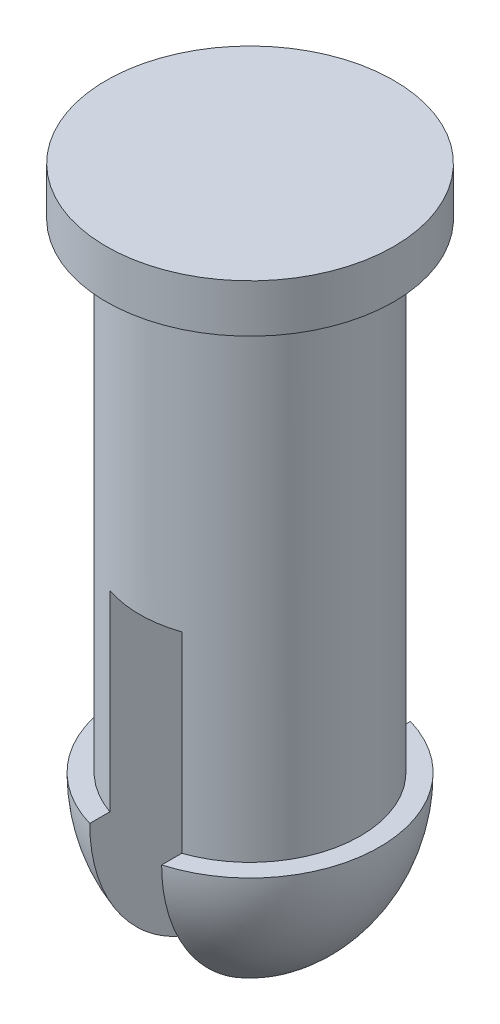
SolidWorks part; units mm, degrees
material "PVC Rigid"
ref_plane "Front Plane" through (0, 0, 0) normal (0, 0, 1) x (1, 0, 0)
ref_plane "Top Plane" through (0, 0, 0) normal (0, 1, 0) x (1, 0, 0)
ref_plane "Right Plane" through (0, 0, 0) normal (1, 0, 0) x (0, 0, -1)
sketch "Sketch1" plane through (0, 0, 0) normal (0, 0, 1) x (1, 0, 0)
  line L0 (0, 0) -> (0, 1.651)
  line L1 (0, 1.651) -> (0.381, 1.651)
  line L2 (0.381, 1.651) -> (0.381, 1.524)
  line L3 (0.381, 1.524) -> (0.2921, 1.524)
  line L4 (0.2921, 1.524) -> (0.2921, 0.254)
  line L5 (0.2921, 0.254) -> (0.3429, 0.254)
  line L6 (0, -0.1778) -> (0, 0)
  line L7 (0, -1000) -> (0, 49000) construction
  arc A0 (0.3429, 0.254) -> (0, -0.1778) centre (-0.1004, 0.254) cw
  dimension "D1" = 1.651
  dimension "D2" = 1.27
  dimension "D3" = 0.381
  dimension "D4" = 0.2921
  dimension "D5" = 0.127
  dimension "D6" = 0.0508
  dimension "D7" = 0.1778
revolve "Revolve1" add sketch "Sketch1" angle 360 about L7
sketch "Sketch4" plane through (0, 0, 0) normal (0, 0, 1) x (1, 0, 0)
  line L0 (-0.0952, 0.254) -> (-0.0952, 0.762)
  line L1 (0.3429, 0.254) -> (-0.3429, 0.254) construction
  line L2 (-0.0952, 0.762) -> (0.0952, 0.762)
  line L3 (0.0952, 0.762) -> (0.0953, -0.3302)
  line L4 (0.0953, -0.3302) -> (-0.0952, -0.3302)
  line L5 (-0.0952, -0.3302) -> (-0.0952, 0.254)
  line L6 (0, 0) -> (0, -0.3302) construction
  dimension "D1" = 0.508
  dimension "D2" = 0.1905
  dimension "D3" = 0.3302
extrude "Cut-Extrude11" cut sketch "Sketch4" against normal mid plane 2.54
